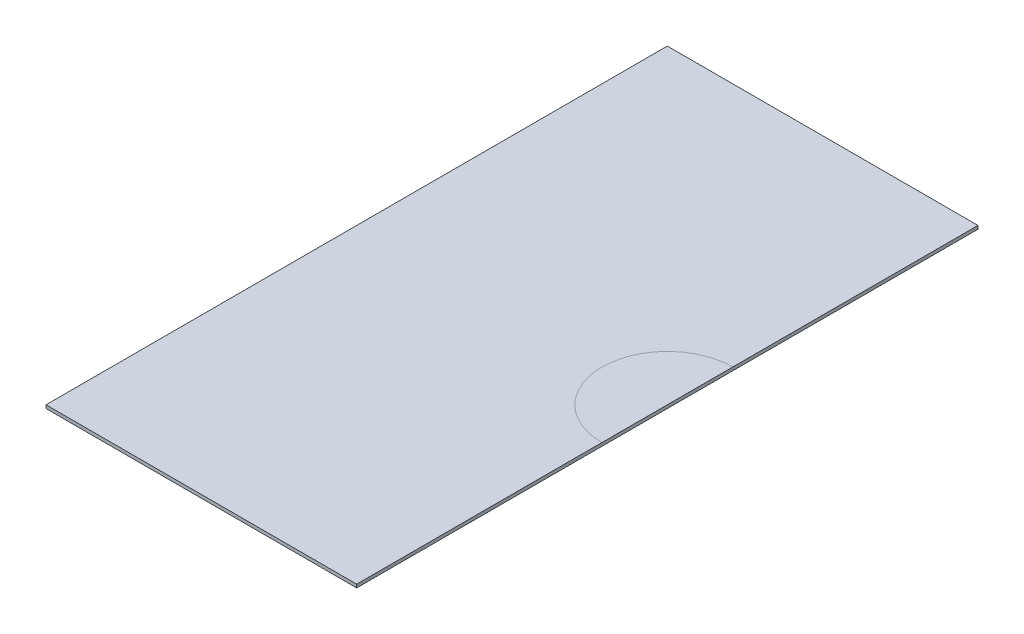
SolidWorks part; units mm, degrees
material "99.5% Aluminum Oxide"
ref_plane "Front Plane" through (0, 0, 0) normal (0, 0, 1) x (1, 0, 0)
ref_plane "Top Plane" through (0, 0, 0) normal (0, 1, 0) x (1, 0, 0)
ref_plane "Right Plane" through (0, 0, 0) normal (1, 0, 0) x (0, 0, -1)
sketch "Sketch1" plane through (0, 0, 0) normal (0, 1, 0) x (1, 0, 0)
  line L1 (-47.5, -95) -> (47.5, -95)
  line L2 (-47.5, -95) -> (-47.5, 95)
  line L3 (-47.5, 95) -> (47.5, 95)
  line L4 (47.5, -95) -> (47.5, 95)
  line L5 (-47.5, -95) -> (47.5, 95) construction
  line L6 (-47.5, 95) -> (47.5, -95) construction
  point P0 (0, 0)
  dimension "D1" = 190
  dimension "D2" = 95
extrude "Boss-Extrude1" add sketch "Sketch1" along normal mid plane 1
sketch "Sketch2" plane through (0, 0.5, 0) normal (0, 1, 0) x (1, 0, 0)
  line L0 (47.5, -95) -> (47.5, 95) construction
  line L1 (47.5, 20) -> (47.5, -20)
  arc A0 (47.5, 20) -> (47.5, -20) centre (47.5, 0) ccw
  dimension "D1" = 20
split line "Split Line1"
equation "\"panel_width\"= 190mm"
equation "\"finger_joint_width\" = 50mm"
equation "\"D1@Sketch1\"=\"panel_width\""
equation "\"D2@Sketch1\"=\"panel_width\"/2"
